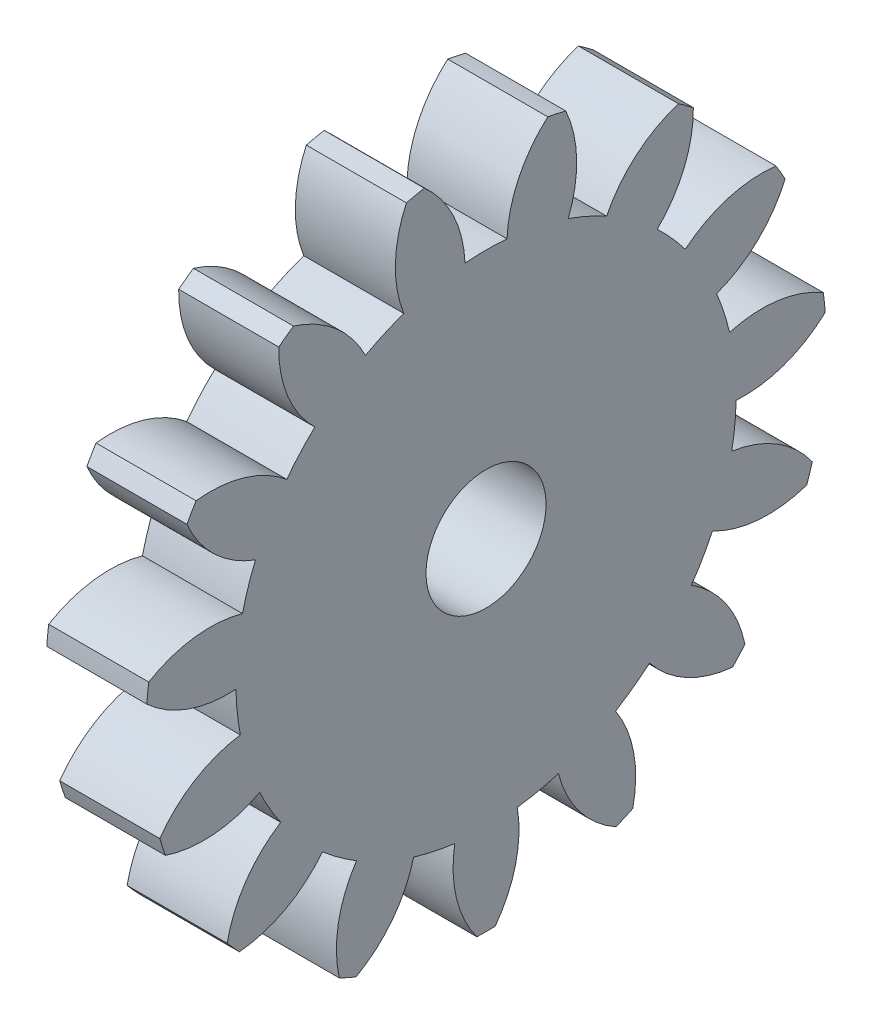
SolidWorks part; units mm, degrees
ref_plane "Plane1" through (0, 0, 0) normal (0, 0, 1) x (1, 0, 0)
ref_plane "Plane2" through (0, 0, 0) normal (0, 1, 0) x (1, 0, 0)
ref_plane "Plane3" through (0, 0, 0) normal (1, 0, 0) x (0, 0, -1)
other "Configuration Table"
sketch "HoldingSke" plane through (0, 0, 0) normal (0, 1, 0) x (1, 0, 0)
  line L0 (0, 0) -> (0.483, -0.1294)
  line L1 (-15, 0) -> (100, 0) construction
  line L2 (0, 0) -> (-2.1039, 2.3779)
  line L3 (0, 0) -> (-11.863, 4.5341)
  line L4 (0, 0) -> (8.3417, 2.2352)
  line L5 (0, 0) -> (-46.8476, -17.4728)
  line L6 (0, 0) -> (-4.1448, -2.7965)
  line L7 (-2.1039, 2.3779) -> (8.6586, 51.2059)
  line L8 (-76.2, 54.61) -> (-75.2, 54.61)
  line L9 (-71.009, 38.7566) -> (-53.1078, 45.2721)
  line L10 (-76.2, 71.12) -> (104.1128, 71.12)
  line L11 (0, 0) -> (-5, 0)
  line L12 (-76.2, 101.6) -> (-76.133, 101.6)
  line L13 (24.9733, 27.94) -> (52.9518, 28.4284)
  line L14 (24.9733, 27.94) -> (24.9743, 27.94)
  line L15 (24.9733, 27.94) -> (100.4006, 29.5858)
  line L16 (-63.627, -2) -> (-12.827, -2)
  circle A0 centre (0, 0) radius 3
  circle A1 centre (0, 0) radius 12.499
  circle A2 centre (0, 0) radius 37.5
  circle A3 centre (0, 0) radius 3
  dimension "MHD" = 24.998
  dimension "Hub_dia" = 75
  dimension "Bore" = 6
  dimension "MBD" = 6
  dimension "Num_teeth" = 15
  dimension "Pitch" = 0.5
  dimension "Overall_len" = 50
  dimension "Show_teeth" = 15
  dimension "Thickness" = 5
  dimension "OAL" = 50.0001
  dimension "T_dim" = 1
  dimension "Ap" = 20
  dimension "H" = 19.05
  dimension "Pitch_radius" = 180.3128
  dimension "Width" = 5
  dimension "Backlash" = 0.067
  dimension "Addendum_fac" = 1
  dimension "Dedendum_fac" = 1.25
  dimension "Clearance_fac" = 0.25
  dimension "Dedendum_add" = 0.001
  dimension "Module" = 2
sketch "BasProSke" plane through (0, 0, 0) normal (0, 1, 0) x (1, 0, 0)
  line L0 (-10, 0) -> (60, 0) construction
  line L1 (0, 0) -> (0, 17)
  line L2 (0, 0) -> (5, 0)
  line L3 (5, 0) -> (5, 17)
  line L4 (5, 17) -> (0, 17)
  dimension "Thickness" = 5
  dimension "Diameter" = 34
revolve "Base-Revolve" add sketch "BasProSke" angle 360 about L0
sketch "TooCutSke" plane through (0, 0, 0) normal (1, 0, 0) x (0, 0, -1)
  line L1 (0, 0) -> (0, 107) construction
  line L2 (0, 0) -> (-1.6851, 14.905) construction
  line L3 (0, 0) -> (-6.2081, 29.2069) construction
  line L4 (-1.6851, 14.905) -> (-3.1041, 14.6034) construction
  arc A0 (1.0501, 12.4548) -> (-1.0501, 12.4548) centre (0, 0) ccw
  arc A1 (3.1109, 16.7388) -> (-3.1109, 16.7388) centre (0, 0) ccw
  circle A2 centre (0, 0) radius 15 construction
  circle A3 centre (0, 0) radius 14.0954 construction
  arc A4 (-1.0501, 12.4548) -> (-3.1109, 16.7388) centre (-7.045, 12.2085) ccw
  arc A5 (3.1109, 16.7388) -> (1.0501, 12.4548) centre (7.045, 12.2085) ccw
  dimension "Root_dia" = 24.998
  dimension "Overcut_dia" = 34.0508
  dimension "Pitch_dia" = 30
  dimension "Base_dia" = 28.1908
  dimension "Flank_rad" = 6
  dimension "Half_ang" = 12
  dimension "Half_CT" = 1.4507
extrude "ToothCut" cut sketch "TooCutSke" along normal through all
fillet "Breaks" [suppressed] radius 0.04
fillet "RootFillets" [suppressed] radius 0.501
pattern_circular "TeethCuts" count 15 every 24 about axis through (-10, 0, 0) along (1, 0, 0) of "ToothCut", "RootFillets", "Breaks"
sketch "HubNeaOneSke" plane through (0, 0, 0) normal (-1, 0, 0) x (0, 0, 1)
  circle A0 centre (0, 0) radius 12.499
  dimension "Diameter" = 24.998
extrude "HubNearOne" [suppressed] add sketch "HubNeaOneSke" along normal blind 45.0001
sketch "HubNeaBotSke" plane through (0, 0, 0) normal (-1, 0, 0) x (0, 0, 1)
  circle A0 centre (0, 0) radius 12.499
  dimension "Diameter" = 24.998
extrude "HubNearBoth" [suppressed] add sketch "HubNeaBotSke" along normal blind 22.5
ref_plane "FarPln" through (5, 0, 0) normal (1, 0, 0) x (0, 0, -1)
sketch "HubFarSke" plane through (5, 0, 0) normal (1, 0, 0) x (0, 0, -1)
  circle A0 centre (0, 0) radius 12.499
  dimension "Diameter" = 24.998
extrude "HubFar" [suppressed] add sketch "HubFarSke" along normal blind 22.5
sketch "BorSke" plane through (0, 0, 0) normal (1, 0, 0) x (0, 0, -1)
  circle A0 centre (0, 0) radius 3
  dimension "Diameter" = 6
extrude "Bore" cut sketch "BorSke" along normal mid plane 100.0001
sketch "KeySke" plane through (0, 0, 0) normal (1, 0, 0) x (0, 0, -1)
  line L0 (-1, 0) -> (-1, 4)
  line L1 (-1, 4) -> (1, 4)
  line L2 (1, 4) -> (1, 0)
  line L3 (0, 0) -> (0, 34) construction
  line L4 (-1, 0) -> (1, 0)
  dimension "Offset" = 4
  dimension "Width" = 2
extrude "Keyway" [suppressed] cut sketch "KeySke" along normal mid plane 100.0001
pattern_circular "Keyway2" [suppressed] count 2 every 90 about axis through (-10, 0, 0) along (1, 0, 0)
equation "' \"Module@HoldingSke\" = 6.35"
equation "' \"Num_teeth@HoldingSke\" = 12"
equation "' \"Ap@HoldingSke\" =  20"
equation "' \"Ap@HoldingSke\" = 20"
equation "' \"Width@HoldingSke\" = 0.5 * 25.4"
equation "' \"Hub_dia@HoldingSke\"= 1 * 25.4"
equation "' \"Hub_dia@HoldingSke\" = 1 * 25.4"
equation "' \"Overall_len@HoldingSke\" = 1.0 * 25.4"
equation "' \"Bore@HoldingSke\" = 0.75 * 25.4"
equation "' \"T_dim@HoldingSke\" = 0.1 * 25.4"
equation "' \"Width@KeySke\" = 0.25 * 25.4"
equation "' \"Show_teeth@HoldingSke\" = 13"
equation "' \"Backlash@HoldingSke\" = 0.009 * 25.4"
equation "' \"Addendum_fac@HoldingSke\" = 1.0"
equation "' \"Dedendum_fac@HoldingSke\" = 1.25"
equation "' \"Dedendum_add@HoldingSke\" = 0.00005 * 25.4"
equation "' \"Clearance_fac@HoldingSke\" = 0.25"
equation "\"Pitch@HoldingSke\" = 1 / \"Module@HoldingSke\""
equation "\"Overcut_dia@TooCutSke\" = (\"Num_teeth@HoldingSke\" + 2 * \"Addendum_fac@HoldingSke\") / \"Pitch@HoldingSke\" + 0.002 * 25.4"
equation "\"Pitch_dia@TooCutSke\" = \"Num_teeth@HoldingSke\" / \"Pitch@HoldingSke\""
equation "\"Base_dia@TooCutSke\" = \"Num_teeth@HoldingSke\" / \"Pitch@HoldingSke\" * cos((\"Ap@HoldingSke\"  * 3.14159265 / 180))"
equation "\"Root_dia@TooCutSke\" = (\"Num_teeth@HoldingSke\" + 2) / \"Pitch@HoldingSke\" - 2 * (\"Addendum_fac@HoldingSke\" + \"Dedendum_fac@HoldingSke\") / \"Pitch@HoldingSke\" - \"Dedendum_add@HoldingSke\" * 2"
equation "\"Half_ang@TooCutSke\" = 180 / \"Num_teeth@HoldingSke\""
equation "\"Half_CT@TooCutSke\" = \"Num_teeth@HoldingSke\" / \"Pitch@HoldingSke\" * sin((3.14159265 / 2 / \"Num_teeth@HoldingSke\")) / 2 - 7 * \"Backlash@HoldingSke\" / 4"
equation "\"Flank_rad@TooCutSke\" = \"Num_teeth@HoldingSke\" / \"Pitch@HoldingSke\" / 5"
equation "\"Radius@RootFillets\" = \"Clearance_fac@HoldingSke\" / \"Pitch@HoldingSke\" + \"Dedendum_add@HoldingSke\""
equation "\"Break_rad@Breaks\" = 0.02 / \"Pitch@HoldingSke\""
equation "\"Thickness@HoldingSke\" = \"Width@HoldingSke\""
equation "\"OAL@HoldingSke\" = \"Thickness@HoldingSke\""
equation "\"MHD@HoldingSke\" = (\"Num_teeth@HoldingSke\" + 2) / \"Pitch@HoldingSke\" - 2 * (\"Addendum_fac@HoldingSke\" + \"Dedendum_fac@HoldingSke\")  / \"Pitch@HoldingSke\" - \"Dedendum_add@HoldingSke\" * 2"
equation "\"MBD@HoldingSke\" = (\"Num_teeth@HoldingSke\" + 2) / \"Pitch@HoldingSke\" - 2 * (\"Addendum_fac@HoldingSke\" + \"Dedendum_fac@HoldingSke\")  / \"Pitch@HoldingSke\" - \"Dedendum_add@HoldingSke\" * 2 - 0.002 * 25.4"
equation "\"MHD@HoldingSke\" = ((sgn( \"MHD@HoldingSke\" - \"Hub_dia@HoldingSke\" )-1)*( \"MHD@HoldingSke\" - \"Hub_dia@HoldingSke\" ))/-2+ \"Hub_dia@HoldingSke\""
equation "\"MBD@HoldingSke\" = ((sgn( \"MBD@HoldingSke\" - \"Bore@HoldingSke\" )-1)*( \"MBD@HoldingSke\" - \"Bore@HoldingSke\" ))/-2+ \"Bore@HoldingSke\""
equation "\"OAL@HoldingSke\" = ((sgn( \"OAL@HoldingSke\" - \"Overall_len@HoldingSke\" )+1)*( \"OAL@HoldingSke\" - \"Overall_len@HoldingSke\" ))/2 + \"Overall_len@HoldingSke\" + 0.000002 * 25.4"
equation "\"Num_teeth@TeethCuts\" = int( \"Show_teeth@HoldingSke\" ) + 1"
equation "\"Num_teeth@TeethCuts\" = ((sgn( \"Num_teeth@TeethCuts\" - \"Num_teeth@HoldingSke\" )-1)*( \"Num_teeth@TeethCuts\" - \"Num_teeth@HoldingSke\" ))/-2+ \"Num_teeth@HoldingSke\""
equation "\"Num_teeth@TeethCuts\" = ((sgn( \"Num_teeth@TeethCuts\" - 2.0)+1)*( \"Num_teeth@TeethCuts\" - 2.0))/2 +2.0"
equation "\"Angle@TeethCuts\" = 360.0 / \"Num_teeth@HoldingSke\""
equation "\"Diameter@BasProSke\" = (\"Num_teeth@HoldingSke\" + 2 * \"Addendum_fac@HoldingSke\") / \"Pitch@HoldingSke\""
equation "\"Thickness@BasProSke\"  = \"Thickness@HoldingSke\""
equation "' \"Fillet_rad@BasProSke\" =  \"Thickness@HoldingSke\" * 0.05"
equation "' \"Fillet_rad@BasProSke\" = \"Thickness@HoldingSke\" * 0.05"
equation "\"MHD@HoldingSke\" = ((sgn( \"MHD@HoldingSke\" - \"Root_dia@TooCutSke\" )-1)*( \"MHD@HoldingSke\" - \"Root_dia@TooCutSke\" ))/-2+ \"Root_dia@TooCutSke\""
equation "\"Diameter@HubNeaOneSke\" = \"MHD@HoldingSke\""
equation "\"Length@HubNearOne\" = \"OAL@HoldingSke\" - \"Thickness@BasProSke\""
equation "\"Diameter@HubNeaBotSke\" = \"MHD@HoldingSke\""
equation "\"Length@HubNearBoth\" = ( \"OAL@HoldingSke\" - \"Thickness@BasProSke\" ) / 2.0"
equation "\"Thickness@FarPln\" = \"Thickness@BasProSke\""
equation "\"Diameter@HubFarSke\" = \"MHD@HoldingSke\""
equation "\"Length@HubFar\" = ( \"OAL@HoldingSke\" - \"Thickness@BasProSke\" ) / 2.0"
equation "\"Diameter@BorSke\" = \"MBD@HoldingSke\""
equation "\"D1@Bore\" = \"OAL@HoldingSke\" * 2.0"
equation "\"D1@Keyway\" = \"OAL@HoldingSke\" * 2.0"
equation "\"Offset@KeySke\" = \"T_dim@HoldingSke\" + \"MBD@HoldingSke\" / 2.0"
